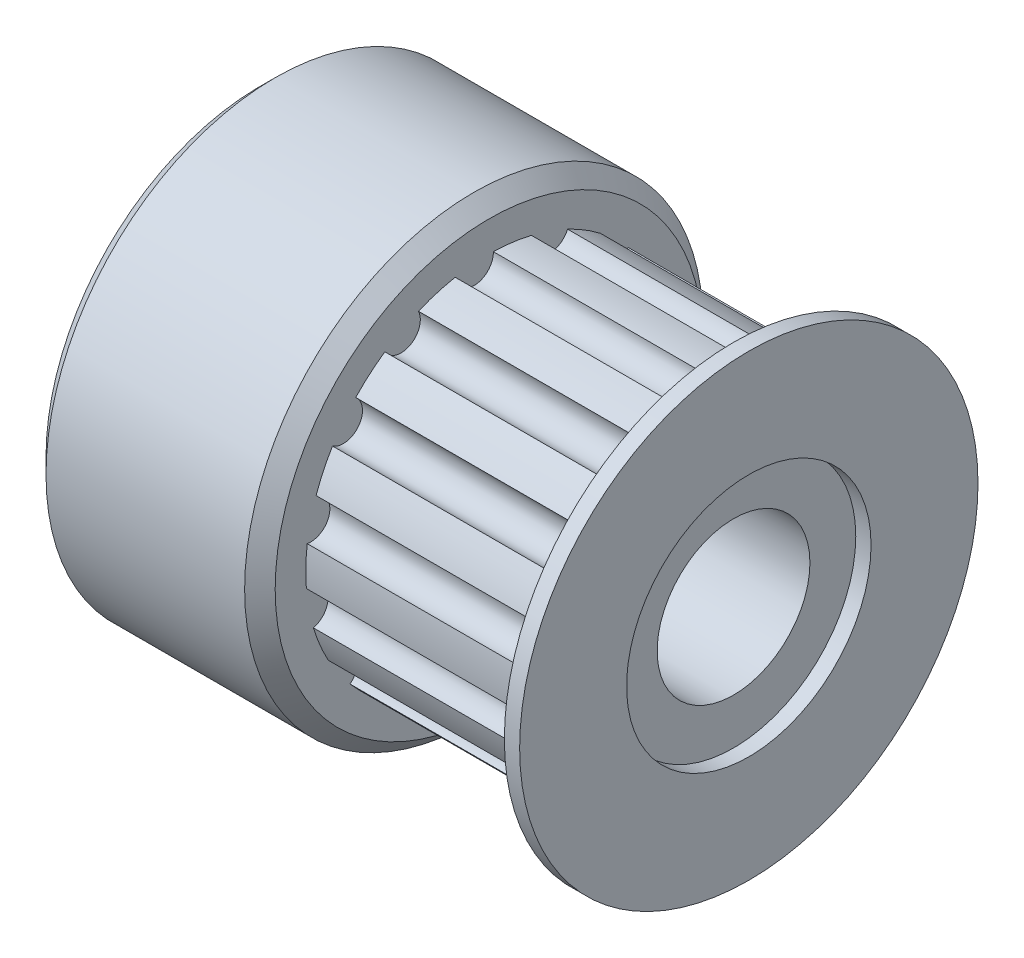
SolidWorks part; units mm, degrees
material "3.0205 (EN-AW 1200)"
ref_plane "Alzado" through (0, 0, 0) normal (0, 0, 1) x (1, 0, 0)
ref_plane "Planta" through (0, 0, 0) normal (0, 1, 0) x (1, 0, 0)
ref_plane "Vista lateral" through (0, 0, 0) normal (1, 0, 0) x (0, 0, -1)
ref_plane "Plano1" through (0, 0, -121.3377) normal (0, 0, 1) x (1, 0, 0)
sketch "Croquis1" plane through (0, 0, -121.3377) normal (0, 0, 1) x (1, 0, 0)
  line L0 (80.1917, -123.9708) -> (80.1917, -131.4708)
  line L1 (80.1917, -131.4708) -> (80.6917, -131.4708)
  line L2 (80.6917, -131.4708) -> (80.6917, -123.9708)
  line L3 (80.6917, -123.9708) -> (80.1917, -123.9708)
  line L4 (80.1917, -131.4708) -> (80.6917, -131.4708) construction
revolve "Revolución1" add sketch "Croquis1" angle 360 about L4
sketch "Croquis2" plane through (80.1917, 0, 0) normal (-1, 0, 0) x (0, 0, 1)
  arc A0 (-121.4772, -125.4724) -> (-120.2287, -125.5742) centre (-120.8503, -125.4906) ccw
  arc A1 (-120.2287, -125.5742) -> (-119.0254, -125.9343) centre (-121.3377, -131.4708) cw
  arc A2 (-119.0254, -125.9343) -> (-117.9262, -126.535) centre (-118.4601, -126.2059) ccw
  arc A3 (-117.9262, -126.535) -> (-116.9734, -127.3534) centre (-121.3377, -131.4708) cw
  arc A4 (-116.9734, -127.3534) -> (-116.2136, -128.3493) centre (-116.5674, -127.8315) ccw
  arc A5 (-116.2136, -128.3493) -> (-115.676, -129.4845) centre (-121.3377, -131.4708) cw
  arc A6 (-115.676, -129.4845) -> (-115.387, -130.7034) centre (-115.4996, -130.0864) ccw
  arc A7 (-115.387, -130.7034) -> (-115.3576, -131.9591) centre (-121.3377, -131.4708) cw
  arc A8 (-115.3576, -131.9591) -> (-115.5893, -133.1901) centre (-115.4413, -132.5806) ccw
  arc A9 (-115.5893, -133.1901) -> (-116.0732, -134.3492) centre (-121.3377, -131.4708) cw
  arc A10 (-116.0732, -134.3492) -> (-116.7856, -135.3795) centre (-116.4025, -134.883) ccw
  arc A11 (-116.7856, -135.3795) -> (-117.6991, -136.2416) centre (-121.3377, -131.4708) cw
  arc A12 (-117.6991, -136.2416) -> (-118.769, -136.8931) centre (-118.2511, -136.5393) ccw
  arc A13 (-118.769, -136.8931) -> (-119.9542, -137.3091) centre (-121.3377, -131.4708) cw
  arc A14 (-119.9542, -137.3091) -> (-121.1965, -137.4691) centre (-120.5795, -137.3566) ccw
  arc A15 (-121.1965, -137.4691) -> (-122.4484, -137.3671) centre (-121.3377, -131.4708) cw
  arc A16 (-122.4484, -137.3671) -> (-123.6485, -137.0079) centre (-123.0579, -137.2189) ccw
  arc A17 (-123.6485, -137.0079) -> (-124.7506, -136.4055) centre (-121.3377, -131.4708) cw
  arc A18 (-124.7506, -136.4055) -> (-125.7009, -135.5894) centre (-125.2044, -135.9726) ccw
  arc A19 (-125.7009, -135.5894) -> (-126.4627, -134.5907) centre (-121.3377, -131.4708) cw
  arc A20 (-126.4627, -134.5907) -> (-126.9988, -133.4586) centre (-126.7012, -134.0107) ccw
  arc A21 (-126.9988, -133.4586) -> (-127.2887, -132.2365) centre (-121.3377, -131.4708) cw
  arc A22 (-127.2887, -132.2365) -> (-127.318, -130.9842) centre (-127.3361, -131.6111) ccw
  arc A23 (-127.318, -130.9842) -> (-127.0856, -129.7498) centre (-121.3377, -131.4708) cw
  arc A24 (-127.0856, -129.7498) -> (-126.603, -128.5939) centre (-126.8746, -129.1592) ccw
  arc A25 (-126.603, -128.5939) -> (-125.8887, -127.5607) centre (-121.3377, -131.4708) cw
  arc A26 (-125.8887, -127.5607) -> (-124.9777, -126.701) centre (-125.4557, -127.107) ccw
  arc A27 (-124.9777, -126.701) -> (-123.9049, -126.0477) centre (-121.3377, -131.4708) cw
  arc A28 (-123.9049, -126.0477) -> (-122.7229, -125.6329) centre (-123.3248, -125.8094) ccw
  arc A29 (-122.7229, -125.6329) -> (-121.4772, -125.4724) centre (-121.3377, -131.4708) cw
extrude "Saliente-Extruir1" add sketch "Croquis2" along normal blind 8
ref_plane "Plano2" through (72.1917, 0, 0) normal (1, 0, 0) x (0, 0, -1)
sketch "Croquis3" plane through (72.1917, 0, 0) normal (1, 0, 0) x (0, 0, -1)
  circle A0 centre (121.3377, -131.4708) radius 7.5
extrude "Saliente-Extruir2" add sketch "Croquis3" against normal blind 7.5
hole_wizard "Taladro roscado M8x1.01" positions "Croquis5" profile "Croquis4" tap size "M8x1.0" standard "Ansi Metric"
sketch "Croquis5" plane through (80.6917, 0, 0) normal (1, 0, 0) x (0, 0, -1)
  point P0 (121.3377, -131.4708)
sketch "Croquis4" plane through (80.6917, -131.4708, -121.3377) normal (0, 1, 0) x (0, 0, -1)
  line L0 (0, 0) -> (0, 16)
  line L1 (0, 16) -> (2.5, 16)
  line L3 (2.5, 16) -> (2.5, 0.5)
  line L4 (2.5, 0.5) -> (4, 0.5)
  line L5 (4, 0.5) -> (4, 0)
  line L7 (4, 0) -> (0, 0)
  line L11 (0, -6.35) -> (0, 107.95) construction
  dimension "Diámetro de perforador para roscar hasta el siguiente" = 5
  dimension "Profundidad de perforador para roscar hasta el siguiente" = 16
  dimension "Diámetro mayor de rosca" = 8
  dimension "Profundidad de rosca" = 0.5
hole_wizard "Diámetro de taladro Ø2.0 (2)1" positions "Croquis3D1" profile "Croquis6" hole size "Ø2.0" standard "Ansi Metric"
sketch3d "Croquis3D1"
  point P0 (69.7273, -135.1691, -127.8625)
sketch "Croquis6" plane through (69.7273, -135.1691, -127.8625) normal (1, 0, 0) x (0, 0.87, -0.4931)
  line L0 (0, 0) -> (0, 5)
  line L1 (0, 5) -> (1, 5)
  line L2 (1, 5) -> (1, 0)
  line L5 (1, 0) -> (0, 0)
  line L11 (0, -6.35) -> (0, 107.95) construction
  dimension "Diámetro de taladro hasta el siguiente" = 2
  dimension "Profundidad de taladro hasta el siguiente" = 5
ref_plane "Plano3" through (0, -138.9708, 0) normal (0, -1, 0) x (-1, 0, 0)
hole_wizard "Diámetro de taladro Ø2.0 (2)2" positions "Croquis8" profile "Croquis7" hole size "Ø2.0" standard "Ansi Metric"
sketch "Croquis8" plane through (0, -138.9708, 0) normal (0, -1, 0) x (-1, 0, 0)
  point P0 (-69.7273, 121.3972)
sketch "Croquis7" plane through (69.7273, -138.9708, -121.3972) normal (1, 0, 0) x (0, 0, -1)
  line L0 (0, 0) -> (0, 5.0007)
  line L1 (0, 5.0007) -> (1, 5.0007)
  line L2 (1, 5.0007) -> (1, 0)
  line L5 (1, 0) -> (0, 0)
  line L11 (0, -6.35) -> (0, 107.95) construction
  dimension "Diámetro de taladro hasta el siguiente" = 2
  dimension "Profundidad de taladro hasta el siguiente" = 5.0007
chamfer "Chaflán1" distance 0.5 angle 45 2 edges at (64.6917, -131.4708, -113.8377) (72.1917, -131.4708, -113.8377)
